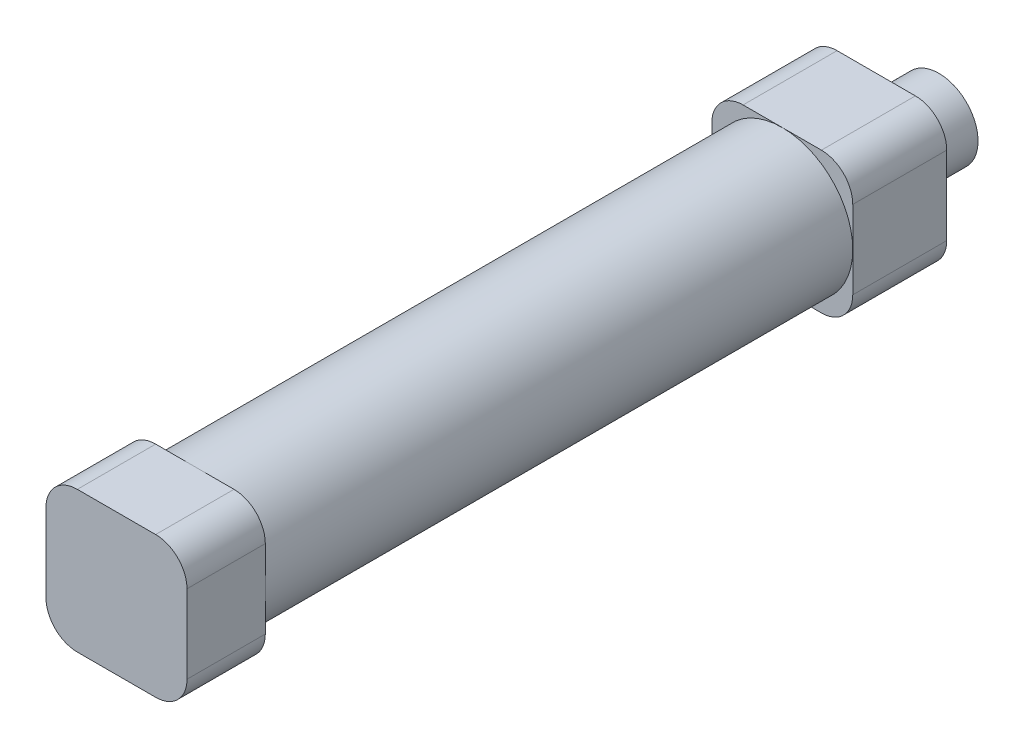
SolidWorks part; units mm, degrees
ref_plane "前视基准面" through (0, 0, 0) normal (0, 0, 1) x (1, 0, 0)
ref_plane "上视基准面" through (0, 0, 0) normal (0, 1, 0) x (1, 0, 0)
ref_plane "右视基准面" through (0, 0, 0) normal (1, 0, 0) x (0, 0, -1)
sketch "草图1" plane through (0, 0, 0) normal (0, 0, 1) x (1, 0, 0)
  circle A0 centre (0, 0) radius 9
  circle A1 centre (0, 0) radius 8
  dimension "D1" = 18
  dimension "D2" = 16
extrude "凸台-拉伸1" add sketch "草图1" along normal blind 75
sketch "草图2" plane through (0, 0, 75) normal (0, 0, 1) x (1, 0, 0)
  line L1 (-5, -9) -> (5, -9)
  line L2 (-9, -5) -> (-9, 5)
  line L3 (-5, 9) -> (5, 9)
  line L4 (9, -5) -> (9, 5)
  line L5 (-9, -9) -> (9, 9) construction
  line L6 (-9, 9) -> (9, -9) construction
  arc A0 (-5, 9) -> (-9, 5) centre (-5, 5) ccw
  arc A1 (9, 5) -> (5, 9) centre (5, 5) ccw
  arc A2 (9, -5) -> (5, -9) centre (5, -5) cw
  arc A3 (-9, -5) -> (-5, -9) centre (-5, -5) ccw
  point P0 (0, 0)
  dimension "D3" = 4
  dimension "D4" = 4
  dimension "D5" = 4
  dimension "D6" = 4
  dimension "D1" = 18
  dimension "D2" = 18
extrude "凸台-拉伸2" add sketch "草图2" along normal blind 10
sketch "草图3" plane through (0, 0, 0) normal (0, 0, -1) x (-1, 0, 0)
  line L1 (-5, -9) -> (5, -9)
  line L2 (-9, -5) -> (-9, 5)
  line L3 (-5, 9) -> (5, 9)
  line L4 (9, -5) -> (9, 5)
  line L5 (-9, -9) -> (9, 9) construction
  line L6 (-9, 9) -> (9, -9) construction
  arc A0 (-9, -5) -> (-5, -9) centre (-5, -5) ccw
  arc A1 (5, -9) -> (9, -5) centre (5, -5) ccw
  arc A2 (9, 5) -> (5, 9) centre (5, 5) ccw
  arc A3 (-5, 9) -> (-9, 5) centre (-5, 5) ccw
  point P0 (0, 0)
  dimension "D3" = 4
  dimension "D1" = 18
  dimension "D2" = 18
extrude "凸台-拉伸3" add sketch "草图3" along normal blind 12
sketch "草图4" plane through (0, 0, -12) normal (0, 0, -1) x (-1, 0, 0)
  circle A0 centre (0, 0) radius 5
extrude "凸台-拉伸4" add sketch "草图4" along normal blind 8
sketch "草图5" plane through (0, 0, -20) normal (0, 0, -1) x (-1, 0, 0)
  circle A0 centre (0, 0) radius 2.5
extrude "切除-拉伸1" cut sketch "草图5" against normal blind 38
sketch "草图6" plane through (-9, 0, 0) normal (-1, 0, 0) x (0, 0, 1)
  line L0 (0, -9) -> (0, 9) construction
  line L1 (75, -5) -> (75, -9) construction
  circle A0 centre (-4, 0) radius 2
  circle A1 centre (79, 0) radius 1.9805
  point P6 (75, -7)
  dimension "D1" = 4
  dimension "D2" = 4
extrude "切除-拉伸3" cut sketch "草图6" against normal blind 3
